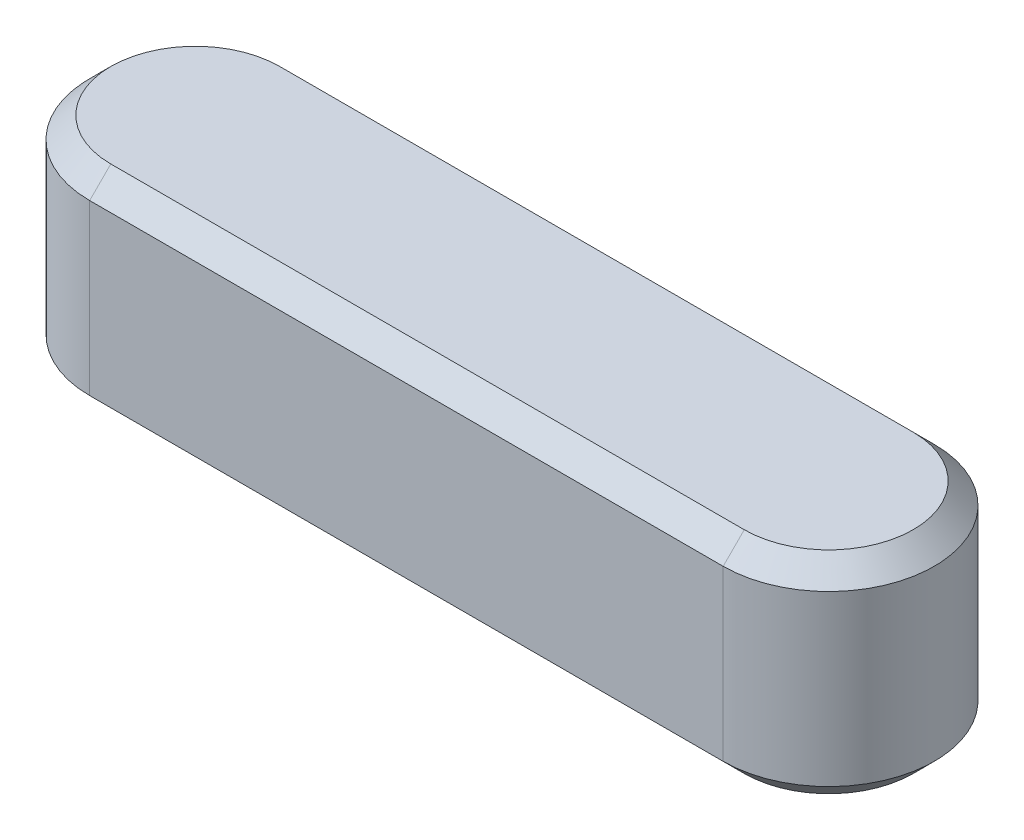
SolidWorks part; units mm, degrees
ref_plane "Front" through (0, 0, 0) normal (0, 0, 1) x (1, 0, 0)
ref_plane "Top" through (0, 0, 0) normal (0, 1, 0) x (1, 0, 0)
ref_plane "Right" through (0, 0, 0) normal (1, 0, 0) x (0, 0, -1)
sketch "Sketch1" plane through (0, 0, 0) normal (0, 1, 0) x (1, 0, 0)
  line L0 (0, 0) -> (6, 0) construction
  line L1 (0, 1) -> (6, 1)
  line L2 (0, -1) -> (6, -1)
  arc A0 (0, 1) -> (0, -1) centre (0, 0) ccw
  arc A1 (6, -1) -> (6, 1) centre (6, 0) ccw
  point P3 (3, 0)
  dimension "D1" = 1
  dimension "D2" = 6
extrude "Boss-Extrude1" add sketch "Sketch1" along normal blind 2
chamfer "Chamfer1" distance 0.2 angle 45 8 edges at (3, 0, 1) (7, 0, 0) (3, 0, -1) (-1, 0, 0) (3, 2, -1) (7, 2, 0) (3, 2, 1) (-1, 2, 0)
